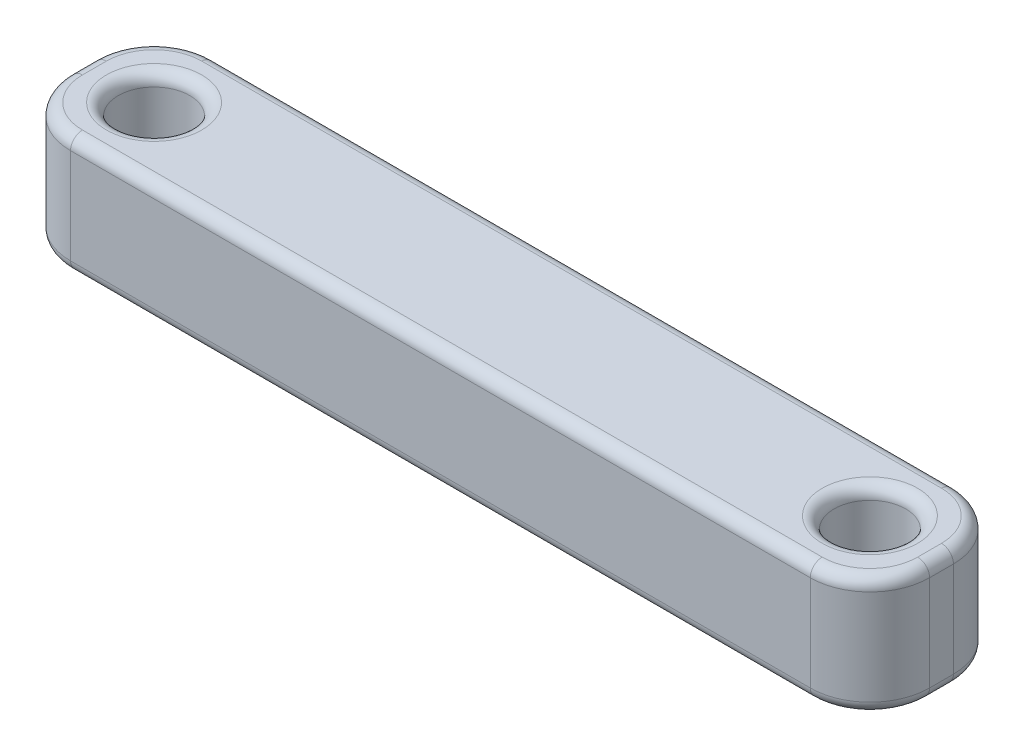
SolidWorks part; units mm, degrees
ref_plane "Front Plane" through (0, 0, 0) normal (0, 0, 1) x (1, 0, 0)
ref_plane "Top Plane" through (0, 0, 0) normal (0, 1, 0) x (1, 0, 0)
ref_plane "Right Plane" through (0, 0, 0) normal (1, 0, 0) x (0, 0, -1)
sketch "Sketch1" plane through (0, 0, 0) normal (0, 1, 0) x (1, 0, 0)
  line L1 (-18, -3) -> (18, -3)
  line L2 (-18, -3) -> (-18, 3)
  line L3 (-18, 3) -> (18, 3)
  line L4 (18, -3) -> (18, 3)
  line L5 (-18, -3) -> (18, 3) construction
  line L6 (-18, 3) -> (18, -3) construction
  point P0 (0, 0)
  dimension "D1" = 36
  dimension "D2" = 6
extrude "Boss-Extrude1" add sketch "Sketch1" along normal blind 5
sketch "Sketch2" plane through (0, 5, 0) normal (0, 1, 0) x (1, 0, 0)
  line L0 (-18, 3) -> (-18, -3) construction
  line L1 (18, -3) -> (18, 3) construction
  circle A0 centre (-15, 0) radius 1.5
  circle A1 centre (15, 0) radius 1.5
  point P7 (-18, 0)
  point P11 (18, 0)
  dimension "D1" = 3
  dimension "D3" = 3
  dimension "D2" = 3
extrude "Cut-Extrude1" cut sketch "Sketch2" against normal through all
fillet "Fillet1" radius 2.5 4 edges at (18, 2.5, -3) (18, 2.5, 3) (-18, 2.5, -3) (-18, 2.5, 3)
fillet "Fillet2" radius 0.5 20 edges at (-17.2678, 0, -2.2678) (-17.2678, 0, 2.2678) (0, 0, 3) (17.2678, 0, 2.2678) (17.2678, 0, -2.2678) (0, 0, -3) (15, 0, 1.5) (-15, 0, 1.5) (0, 5, 3) (-17.2678, 5, 2.2678) (-17.2678, 5, -2.2678) (0, 5, -3) (17.2678, 5, -2.2678) (17.2678, 5, 2.2678) (15, 5, 1.5) (-15, 5, 1.5) (-18, 0, 0) (18, 0, 0) (-18, 5, 0) (18, 5, 0)
